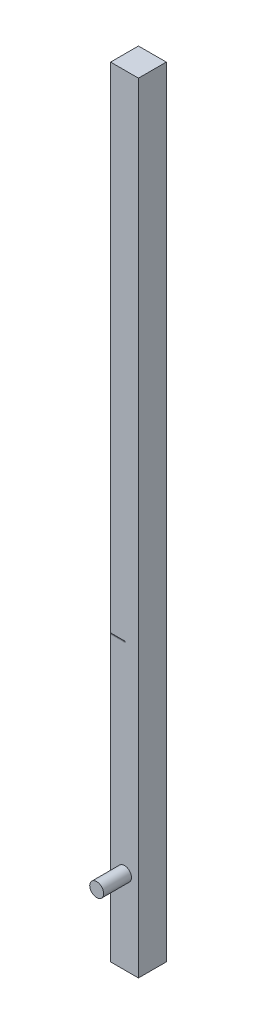
SolidWorks part; units mm, degrees
material "Thornel Mat VMA"
ref_plane "前视基准面" through (0, 0, 0) normal (0, 0, 1) x (1, 0, 0)
ref_plane "上视基准面" through (0, 0, 0) normal (0, 1, 0) x (1, 0, 0)
ref_plane "右视基准面" through (0, 0, 0) normal (1, 0, 0) x (0, 0, -1)
other "Configuration Table"
sketch "草图1" plane through (0, 0, 0) normal (0, 1, 0) x (1, 0, 0)
  line L1 (-5, 5) -> (5, 5)
  line L2 (-5, 5) -> (-5, -5)
  line L3 (-5, -5) -> (5, -5)
  line L4 (5, 5) -> (5, -5)
  line L5 (-5, 5) -> (5, -5) construction
  line L6 (-5, -5) -> (5, 5) construction
  point P0 (0, 0)
extrude "凸台-拉伸1" add sketch "草图1" along normal blind 280
sketch "草图2" plane through (0, 0, 5) normal (0, 0, 1) x (1, 0, 0)
  line L0 (0, 0) -> (0, 30)
  line L1 (-5, 0) -> (5, 0) construction
  circle A0 centre (0, 30) radius 2.5
extrude "凸台-拉伸2" add sketch "草图2" along normal blind 10
sketch "草图3" plane through (0, 0, 5) normal (0, 0, 1) x (1, 0, 0)
  line L1 (-4.8868, 102.3989) -> (0.4392, 102.3989)
  line L2 (-4.8868, 102.3989) -> (-4.8868, 102.0856)
  line L3 (-4.8868, 102.0856) -> (0.4392, 102.0856)
  line L4 (0.4392, 102.3989) -> (0.4392, 102.0856)
  line L5 (-4.8868, 102.3989) -> (0.4392, 102.0856) construction
  line L6 (-4.8868, 102.0856) -> (0.4392, 102.3989) construction
  point P0 (-2.2238, 102.2423)
extrude "凸台-拉伸3" add sketch "草图3" along normal blind 0.1
